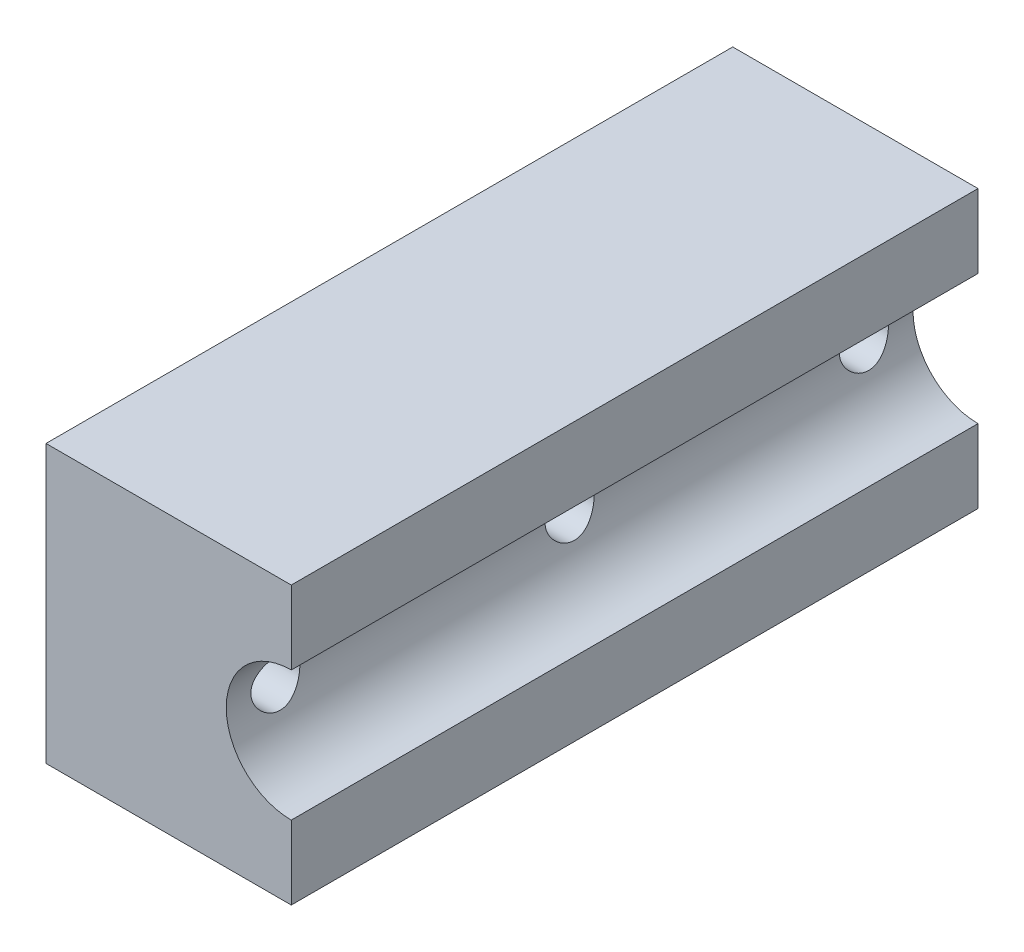
SolidWorks part; units mm, degrees
ref_plane "Front Plane" through (0, 0, 0) normal (0, 0, 1) x (1, 0, 0)
ref_plane "Top Plane" through (0, 0, 0) normal (0, 1, 0) x (1, 0, 0)
ref_plane "Right Plane" through (0, 0, 0) normal (1, 0, 0) x (0, 0, -1)
sketch "Sketch1" plane through (0, 0, 0) normal (0, 0, 1) x (1, 0, 0)
  line L0 (0, 14.125) -> (0, -14.125)
  line L1 (-25, -14.125) -> (25, -14.125)
  line L2 (-25, -14.125) -> (-25, 14.125)
  line L3 (-25, 14.125) -> (25, 14.125)
  line L4 (25, -14.125) -> (25, 14.125)
  line L5 (-25, -14.125) -> (25, 14.125) construction
  line L6 (-25, 14.125) -> (25, -14.125) construction
  circle A0 centre (0, 0) radius 6.625
  circle A1 centre (0, 0) radius 14.125 construction
  dimension "D1" = 13.25
  dimension "D3" = 50
  dimension "D2" = 7.5
extrude "Boss-Extrude1" add sketch "Sketch1" along normal blind 70 contours A0 L0 L3 L2 L1
sketch "Sketch2" plane through (-25, 0, 0) normal (-1, 0, 0) x (0, 0, 1)
  line L0 (0, 0) -> (70, 0) construction
  line L1 (70, -14.125) -> (70, 14.125) construction
  line L2 (0, -14.125) -> (0, 14.125) construction
  circle A0 centre (5, 0) radius 2.5
  circle A1 centre (35, 0) radius 2.5
  circle A2 centre (65, 0) radius 2.5
  dimension "D1" = 5
  dimension "D2" = 5
  dimension "D3" = 5
  dimension "D4" = 30
  dimension "D5" = 30
  dimension "D6" = 5
extrude "Cut-Extrude1" cut sketch "Sketch2" against normal through all
